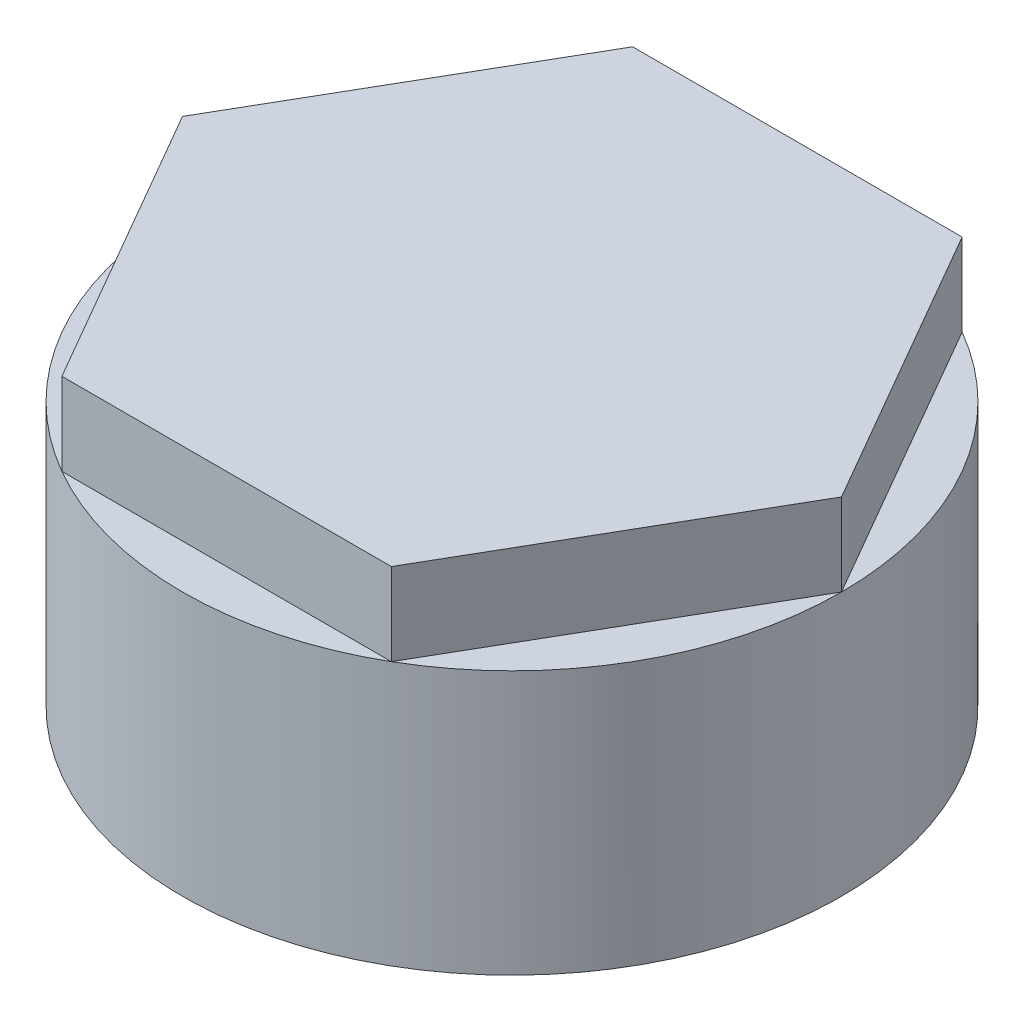
SolidWorks part; units mm, degrees
material "Plain Carbon Steel"
ref_plane "Piano frontale" through (0, 0, 0) normal (0, 0, 1) x (1, 0, 0)
ref_plane "Piano superiore" through (0, 0, 0) normal (0, 1, 0) x (1, 0, 0)
ref_plane "Piano destro" through (0, 0, 0) normal (1, 0, 0) x (0, 0, -1)
sketch "Schizzo1" plane through (0, 0, 0) normal (0, 0, 1) x (1, 0, 0)
  line L0 (-15.5465, 0) -> (-15.5465, 15)
  line L1 (-15.5465, 15) -> (0, 15)
  line L2 (0, 15) -> (0, 21)
  line L3 (0, 21) -> (-20, 21)
  line L4 (-20, 21) -> (-20, 0)
  line L5 (-20, 0) -> (-15.5465, 0)
  line L6 (0, 0) -> (0, 29.0615) construction
  dimension "D1" = 40
  dimension "D2" = 31.093
  dimension "D3" = 21
  dimension "D4" = 15
revolve "Rivoluzione1" add sketch "Schizzo1" angle 360 about L6
cosmetic thread "Filettatura cosmetica1" parameters "D1"=14.9999, "D2"=36
sketch "Schizzo2" plane through (0, 21, 0) normal (0, 1, 0) x (1, 0, 0)
  line L0 (-10, 17.3205) -> (10, 17.3205)
  line L1 (10, 17.3205) -> (20, 0)
  line L2 (20, 0) -> (10, -17.3205)
  line L3 (10, -17.3205) -> (-10, -17.3205)
  line L4 (-10, -17.3205) -> (-20, 0)
  line L5 (-20, 0) -> (-10, 17.3205)
  circle A0 centre (0, 0) radius 20
  circle A1 centre (0, 0) radius 20 construction
  circle M8 centre (0, 0) radius 20
extrude "Taglio-Estrusione1" cut sketch "Schizzo2" against normal blind 5 contours L5 M8 | L4 M8 | L3 M8 | L2 M8 | L1 M8 | L0 M8
equation "\"17.5.00mm\"=5000"
